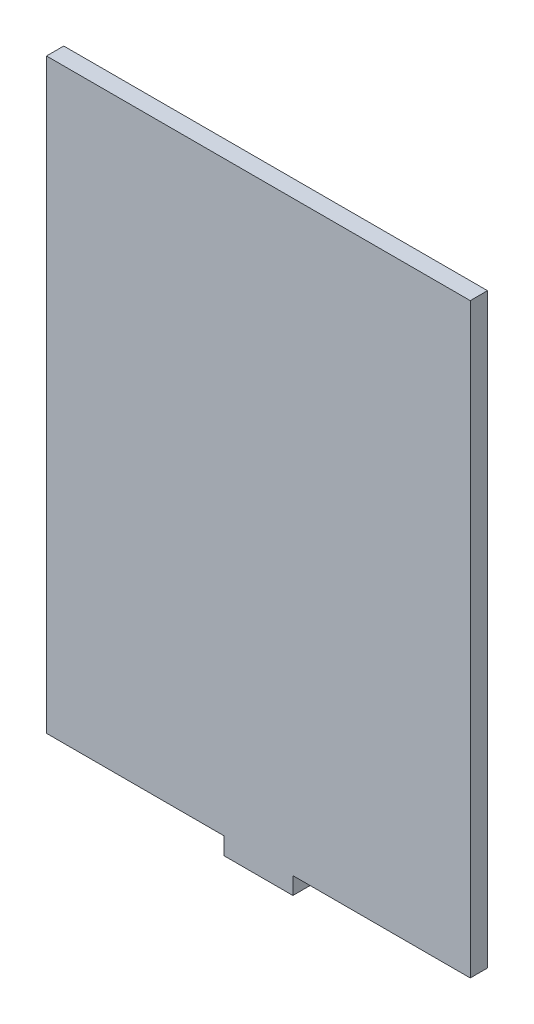
SolidWorks part; units mm, degrees
ref_plane "Front Plane" through (0, 0, 0) normal (0, 0, 1) x (1, 0, 0)
ref_plane "Top Plane" through (0, 0, 0) normal (0, 1, 0) x (1, 0, 0)
ref_plane "Right Plane" through (0, 0, 0) normal (1, 0, 0) x (0, 0, -1)
sketch "Sketch1" plane through (0, 0, 0) normal (0, 0, 1) x (1, 0, 0)
  line L1 (-61.4, -85) -> (-10, -85)
  line L2 (-61.4, -85) -> (-61.4, 85)
  line L3 (-61.4, 85) -> (61.4, 85)
  line L4 (61.4, -85) -> (61.4, 85)
  line L5 (-61.4, -85) -> (61.4, 85) construction
  line L6 (-61.4, 85) -> (61.4, -85) construction
  line L7 (-10, -85) -> (-10, -90)
  line L8 (-10, -90) -> (10, -90)
  line L9 (10, -90) -> (10, -85)
  line L11 (10, -85) -> (61.4, -85)
  point P0 (0, 0)
  point P10 (0, 0)
  dimension "D1" = 122.8
  dimension "D2" = 170
  dimension "D5" = 5
extrude "Boss-Extrude1" add sketch "Sketch1" along normal blind 5
